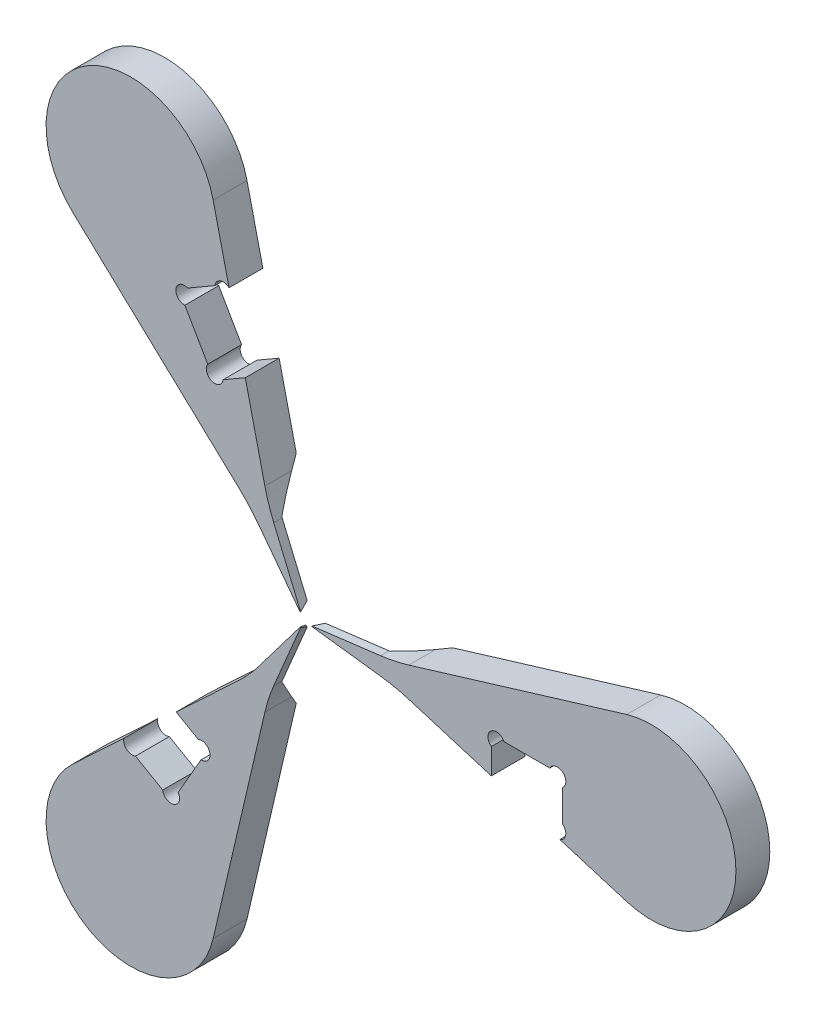
SolidWorks part; units mm, degrees
ref_plane "前基準面" through (0, 0, 0) normal (0, 0, 1) x (1, 0, 0)
ref_plane "上基準面" through (0, 0, 0) normal (0, 1, 0) x (1, 0, 0)
ref_plane "右基準面" through (0, 0, 0) normal (1, 0, 0) x (0, 0, -1)
sketch "草圖1" plane through (0, 0, 0) normal (0, 0, 1) x (1, 0, 0)
  line L0 (0.3574, 0.005) -> (20.1903, 2.4807) construction
  line L1 (20.1903, -2.4807) -> (0.3574, -0.005) construction
  line L2 (0.3574, 0.005) -> (4.5094, 0.5233)
  line L3 (0.3574, -0.005) -> (4.5094, -0.5233)
  line L4 (6.1751, 0.8773) -> (19.0478, 4.7845)
  line L5 (6.1751, -0.8773) -> (19.0478, -4.7845)
  line L6 (-2.3278, -5.7864) -> (-5.3804, -18.8881)
  line L7 (-0.1744, -0.312) -> (-1.8015, -4.1669)
  line L8 (-0.183, -0.307) -> (-2.7079, -3.6436)
  line L9 (-3.8473, -4.9091) -> (-13.6674, -14.1037)
  line L10 (-3.8473, 4.9091) -> (-13.6674, 14.1037)
  line L11 (-0.183, 0.307) -> (-2.7079, 3.6436)
  line L12 (-0.1744, 0.312) -> (-1.8015, 4.1669)
  line L13 (-2.3278, 5.7864) -> (-5.3804, 18.8881)
  line L14 (0.358, 0) -> (20.5, 0) construction
  line L19 (11.0977, -0.2031) -> (15.2977, -0.2031) construction
  line L20 (15.2977, -0.2031) -> (15.2977, -3.3031) construction
  line L21 (11.0977, -0.2031) -> (11.0977, -3.3031) construction
  line L22 (11.0977, -3.3031) -> (15.2977, -3.3031) construction
  line L23 (13.1977, -0.2031) -> (13.1977, -3.3031) construction
  line L24 (11.0977, -1.7531) -> (15.2977, -1.7531) construction
  line L25 (13.1977, -1.7531) -> (11.0977, -0.2031) construction
  circle A0 centre (0, 0) radius 0.353 construction
  arc A1 (0.3574, 0.005) -> (0.3574, -0.005) centre (0.358, 0) ccw
  arc A2 (19.0478, -4.7845) -> (19.0478, 4.7845) centre (20.5, 0) ccw
  circle A3 centre (20.5, 0) radius 2.5 construction
  arc A4 (4.5094, -0.5233) -> (6.1751, -0.8773) centre (3.2707, -10.4463) cw
  arc A5 (4.5094, 0.5233) -> (6.1751, 0.8773) centre (3.2707, 10.4463) ccw
  arc A6 (-13.6674, -14.1037) -> (-5.3804, -18.8881) centre (-10.25, -17.7535) ccw
  arc A7 (-1.8015, -4.1669) -> (-2.3278, -5.7864) centre (7.4114, -8.0556) ccw
  arc A8 (-0.1744, -0.312) -> (-0.183, -0.307) centre (-0.179, -0.31) ccw
  arc A9 (-2.7079, -3.6436) -> (-3.8473, -4.9091) centre (-10.6821, 2.3906) cw
  circle A10 centre (-10.25, -17.7535) radius 2.5 construction
  arc A11 (-5.3804, 18.8881) -> (-13.6674, 14.1037) centre (-10.25, 17.7535) ccw
  arc A12 (-2.7079, 3.6436) -> (-3.8473, 4.9091) centre (-10.6821, -2.3906) ccw
  arc A13 (-0.183, 0.307) -> (-0.1744, 0.312) centre (-0.179, 0.31) ccw
  arc A14 (-1.8015, 4.1669) -> (-2.3278, 5.7864) centre (7.4114, 8.0556) cw
  circle A15 centre (-10.25, 17.7535) radius 2.5 construction
  circle A21 centre (11.5, -0.5) radius 0.5 construction
  circle A22 centre (14.8954, -0.5) radius 0.5 construction
  circle A23 centre (14.8954, -3.0061) radius 0.5 construction
  circle A24 centre (11.5, -3.0061) radius 0.5 construction
  circle A25 centre (13.1977, -0.9631) radius 0.15 construction
  point P18 (5.3574, -0.6291)
  point P21 (5.3574, 0.6291)
  point P48 (0, 0)
  dimension "D1" = 0.706
  dimension "D2" = 0.01
  dimension "D3" = 10
  dimension "D5" = 5
  dimension "D7" = 10
  dimension "D9" = 4.2
  dimension "D11" = 1
  dimension "D12" = 0.3
  dimension "D14" = 11.5
  dimension "D4" = 20.5
  dimension "D6" = 5
  dimension "D10" = 3.1
  dimension "D13" = 0.79
  dimension "D8" = 3
extrude "填料-伸長1" add sketch "草圖1" along normal blind 2
ref_plane "平面1" through (0, 0, 2) normal (0, 0, 1) x (1, 0, 0)
sketch "草圖2" plane through (0, 0, 2) normal (0, 0, 1) x (1, 0, 0)
  line L0 (0, 0) -> (20.5, 0) construction
  line L1 (11.05, -0.2286) -> (15.25, -0.2286)
  line L2 (15.25, -0.2286) -> (15.25, -3.3286)
  line L3 (15.25, -3.3286) -> (11.05, -3.3286)
  line L4 (11.05, -3.3286) -> (11.05, -0.2286)
  line L5 (13.15, -0.2286) -> (13.15, -3.3286) construction
  line L6 (11.05, -1.7786) -> (15.25, -1.7786) construction
  line L7 (13.15, -1.7786) -> (11.05, -0.2286) construction
  line L12 (0, 0) -> (-12.75, 22.0836) construction
  line L13 (-6.575, 11.3882) -> (10.2762, 21.1173) construction
  line L14 (-7.4271, 13.3212) -> (-5.3271, 9.6839)
  line L19 (-7.4271, 13.3212) -> (-4.7424, 14.8712)
  line L20 (-4.7424, 14.8712) -> (-2.6424, 11.2339)
  line L21 (-2.6424, 11.2339) -> (-5.3271, 9.6839)
  line L22 (-6.0847, 14.0962) -> (-3.9847, 10.4589) construction
  line L23 (-4.7424, 14.8712) -> (-5.3271, 9.6839) construction
  line L24 (-7.4271, 13.3212) -> (-2.6424, 11.2339) construction
  line L25 (-4.7841, 14.5007) -> (-3.8841, 12.9418) construction
  line L30 (0, 0) -> (-12.75, -22.0836) construction
  line L31 (-6.575, -11.3882) -> (-30.4249, 2.3815) construction
  line L32 (-5.7229, -9.4553) -> (-7.8229, -13.0926)
  line L33 (-5.7229, -9.4553) -> (-8.4076, -7.9053)
  line L34 (-8.4076, -7.9053) -> (-10.5076, -11.5426)
  line L35 (-10.5076, -11.5426) -> (-7.8229, -13.0926)
  line L36 (-7.0653, -8.6803) -> (-9.1653, -12.3176) construction
  line L37 (-8.4076, -7.9053) -> (-7.8229, -13.0926) construction
  line L38 (-10.5076, -11.5426) -> (-5.7229, -9.4553) construction
  line L39 (-10.1659, -11.3935) -> (-9.2659, -9.8347) construction
  circle A0 centre (11.35, -0.45) radius 0.5
  circle A1 centre (14.95, -0.45) radius 0.5
  circle A2 centre (14.95, -3.1071) radius 0.5
  circle A3 centre (11.35, -3.1071) radius 0.5
  circle A4 centre (14, -3.1071) radius 1.05
  circle A5 centre (13.15, -0.9886) radius 0.15 construction
  arc A11 (-5.3804, 18.8881) -> (-13.6674, 14.1037) centre (-10.25, 17.7535) ccw construction
  circle A17 centre (-7.0853, 13.1721) radius 0.5
  circle A18 centre (-4.7841, 14.5007) radius 0.5
  circle A19 centre (-2.9841, 11.383) radius 0.5
  circle A20 centre (-5.2853, 10.0544) radius 0.5
  circle A21 centre (-4.3091, 13.6779) radius 1.05
  arc A22 (-13.6674, -14.1037) -> (-5.3804, -18.8881) centre (-10.25, -17.7535) ccw construction
  circle A23 centre (-6.0647, -9.6044) radius 0.5
  circle A24 centre (-7.8647, -12.7221) radius 0.5
  circle A25 centre (-10.1659, -11.3935) radius 0.5
  circle A26 centre (-8.3659, -8.2758) radius 0.5
  circle A27 centre (-9.6909, -10.5708) radius 1.05
  point P33 (-6.3771, 11.5025)
  point P57 (-6.7729, -11.2739)
  dimension "D3" = 1
  dimension "D4" = 2.1
  dimension "D6" = 0.3
  dimension "D10" = 13.15
  dimension "D14" = 1
  dimension "D17" = 2.1
  dimension "D22" = 1
  dimension "D25" = 2.1
  dimension "D1" = 4.2
  dimension "D2" = 3.1
  dimension "D5" = 1.25
  dimension "D7" = 0.79
  dimension "D8" = 0.45
  dimension "D9" = 13.15
  dimension "D11" = 4.2
  dimension "D12" = 3.1
  dimension "D13" = 0.3
  dimension "D15" = 0.3
  dimension "D16" = 0.45
  dimension "D18" = 1.25
  dimension "D19" = 13.15
  dimension "D20" = 4.2
  dimension "D21" = 3.1
  dimension "D23" = 0.3
  dimension "D24" = 0.45
  dimension "D26" = 1.25
extrude "除料-伸長1" cut sketch "草圖2" against normal through all
sketch "草圖3" plane through (0, 0, 0) normal (0, 1, 0) x (1, 0, 0)
  line L0 (0, 1.7067) -> (0, -3.5956) construction
  line L1 (0, -1.5) -> (4.6, -1.5)
  line L5 (4.6, -1.5) -> (6.86, 0)
  line L6 (4.5094, 0) -> (0.3574, 0) construction
  line L7 (6.86, 0) -> (0, 0)
  line L8 (0, 0) -> (0, -1.5)
  line L9 (4.5094, -2) -> (0.3574, -2) construction
  dimension "D1" = 4.6
  dimension "D2" = 6.86
  dimension "D3" = 0.5
revolve "除料-旋轉2" cut sketch "草圖3" angle 360 about L0
sketch "草圖4" plane through (0, 0, 0) normal (0, 1, 0) x (1, 0, 0)
  line L0 (0, 0.875) -> (0, -3.0684) construction
  line L1 (0.353, -2.18) -> (0.7456, -1.5)
  line L3 (0.353, -1.5) -> (0.353, -2) construction
  line L4 (0.3574, -1.5) -> (4.5094, -1.5) construction
  line L5 (0.7456, -1.5) -> (0.353, -1.5)
  line L6 (0.353, -1.5) -> (0.353, -2.18)
  line L7 (4.5094, -2) -> (0.3574, -2) construction
  dimension "D1" = 30
  dimension "D2" = 0.18
revolve "除料-旋轉4" cut sketch "草圖4" angle 360 about L0
